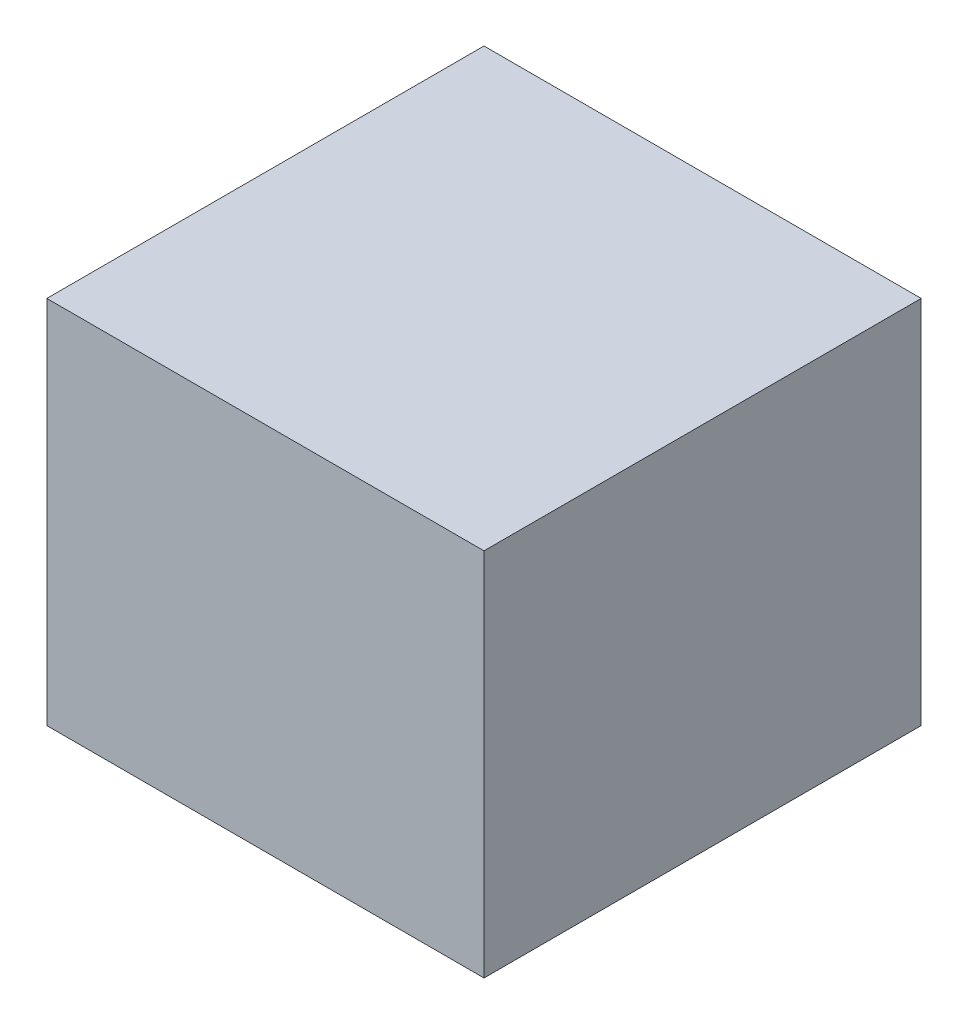
SolidWorks part; units mm, degrees
ref_plane "Front Plane" through (0, 0, 0) normal (0, 0, 1) x (1, 0, 0)
ref_plane "Top Plane" through (0, 0, 0) normal (0, 1, 0) x (1, 0, 0)
ref_plane "Right Plane" through (0, 0, 0) normal (1, 0, 0) x (0, 0, -1)
sketch "Sketch2" plane through (0, 0, 0) normal (0, 1, 0) x (1, 0, 0)
  line L1 (-165.1, 165.1) -> (165.1, 165.1)
  line L2 (-165.1, 165.1) -> (-165.1, -165.1)
  line L3 (-165.1, -165.1) -> (165.1, -165.1)
  line L4 (165.1, 165.1) -> (165.1, -165.1)
  line L5 (-165.1, 165.1) -> (165.1, -165.1) construction
  line L6 (-165.1, -165.1) -> (165.1, 165.1) construction
  point P0 (0, 0)
  dimension "D1" = 330.2
  dimension "D2" = 330.2
extrude "Boss-Extrude1" add sketch "Sketch2" along normal blind 279.4
